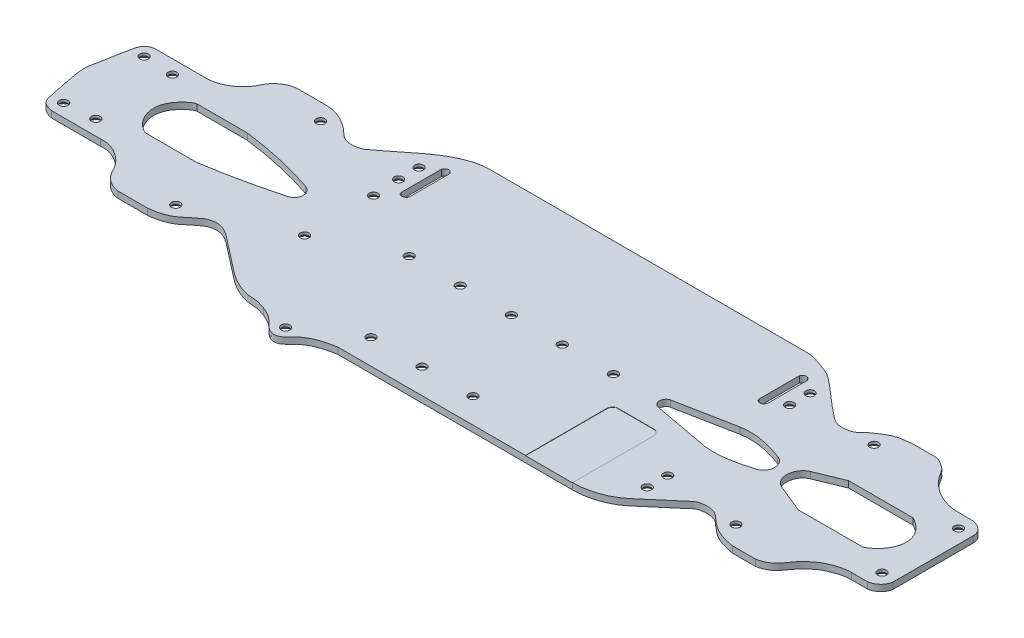
SolidWorks part; units mm, degrees
material "Zoltek Panex 33"
ref_plane "Front Plane" through (0, 0, 0) normal (0, 0, 1) x (1, 0, 0)
ref_plane "Top Plane" through (0, 0, 0) normal (0, 1, 0) x (1, 0, 0)
ref_plane "Right Plane" through (0, 0, 0) normal (1, 0, 0) x (0, 0, -1)
sketch "Sketch1" plane through (0, 0, 0) normal (0, 1, 0) x (1, 0, 0)
  line L0 (36.9075, 54.8824) -> (56.619, 54.8824)
  line L5 (-505.162, 146.0143) -> (342.4194, 309.6238) construction
  line L6 (291.5512, 9.8532) -> (300.5935, 9.8532)
  line L7 (323.9187, 24.1186) -> (330.3042, 24.1186)
  line L8 (335.3376, 29.0345) -> (335.3376, 60.2672)
  line L9 (330.5501, 65.4209) -> (323.8702, 65.4209)
  line L10 (300.1848, 79.7219) -> (292.3112, 79.7219)
  line L11 (62.1058, 79.7259) -> (51.43, 79.7259)
  line L13 (10.7454, 24.1146) -> (29.9596, 24.1146)
  line L14 (51.0209, 9.8532) -> (62.5548, 9.8532)
  line L15 (147.063, -0.0125) -> (238.9152, -0.0125)
  line L16 (116.3922, 89.9875) -> (241.4126, 89.9875)
  line L17 (9.9428, 65.3756) -> (29.4609, 65.3756)
  line L18 (106.9523, 80.6662) -> (106.9523, 64.8635)
  line L19 (110.0606, 80.6662) -> (110.0606, 64.8635)
  line L20 (247.0438, 80.6662) -> (247.0438, 64.8635)
  line L21 (250.1871, 80.6662) -> (250.1871, 64.8635)
  line L22 (220.4502, -0.0125) -> (220.4502, 31.35)
  line L23 (238.9152, -0.0125) -> (238.9152, 31.35)
  line L24 (222, 34.0566) -> (237, 34.0566)
  line L25 (220.4502, -0.0125) -> (238.9152, -0.0125)
  line L27 (56.619, 34.9418) -> (36.9075, 34.9418)
  line L29 (317.5252, 34.9418) -> (292.3112, 34.9418)
  line L31 (292.3112, 54.6841) -> (317.5252, 54.6841)
  line L33 (292.3112, 54.6841) -> (281.6573, 50.3113)
  line L34 (292.3112, 34.9418) -> (281.6573, 39.2887)
  line L35 (2.8407, 44.9982) -> (335.3376, 44.6509)
  circle A7 centre (255.1, 13) radius 1.5
  circle A8 centre (255.1, 21) radius 1.5
  circle A9 centre (255.1, 68.8) radius 1.5
  circle A10 centre (255.1, 76.8) radius 1.5
  circle A11 centre (285.1, 71.85) radius 1.5
  circle A12 centre (285.1, 17.75) radius 1.5
  circle A13 centre (170.1, 9.8) radius 1.5
  circle A14 centre (150.1, 9.8) radius 1.5
  circle A15 centre (150.1, 44.8) radius 1.5
  circle A16 centre (130.1, 44.8) radius 1.5
  circle A17 centre (170.1, 44.8) radius 1.5
  circle A18 centre (190.1, 44.7454) radius 1.5
  circle A19 centre (210.1, 44.8) radius 1.5
  circle A20 centre (130.1, -3.6) radius 1.5
  circle A21 centre (102.6, 31.35) radius 1.5
  circle A22 centre (102.6, 58.35) radius 1.5
  circle A23 centre (102, 68.75) radius 1.5
  circle A24 centre (102, 76.75) radius 1.5
  circle A25 centre (67, 73.2) radius 1.5
  circle A26 centre (67, 16.5) radius 1.5
  circle A27 centre (22.2, 30) radius 1.5
  circle A28 centre (10.5, 29.1) radius 1.5
  circle A29 centre (10.5, 60.6) radius 1.5
  circle A30 centre (22.2, 60) radius 1.5
  circle A32 centre (330, 60) radius 1.5
  circle A33 centre (330, 30) radius 1.5
  circle A34 centre (190.1, 9.8) radius 1.5
  spline S0 degree 3 poles (238.9152, -0.0125) (242.5691, -0.0579) (247.678, 1.0476) (253.755, 4.2222) (257.449, 7.3728) (262.1815, 11.5538) (266.2457, 14.8282) (269.3805, 17.7348) (271.4097, 18.2316) (273.2247, 18.4304) (275.0039, 18.2101) (276.5606, 17.8019) (277.9794, 16.876) (279.2967, 15.7521) (280.6133, 14.5036) (282.0863, 13.2873) (283.8936, 12.1947) (286.9859, 10.7524) (289.6755, 10.2087) (291.5512, 9.8532) knots 0 0 0 0 0.180867 0.249762 0.337799 0.419905 0.561881 0.598784 0.626796 0.663132 0.688826 0.715104 0.741927 0.771676 0.80083 0.831669 0.865959 0.90501 1 1 1 1
  spline S1 degree 3 poles (300.5935, 9.8532) (301.5159, 9.9919) (303.5768, 10.6563) (306.0873, 12.2304) (308.2319, 15.2673) (310.0767, 17.9996) (312.7538, 20.0495) (314.5484, 21.4716) (316.7163, 22.4429) (318.7469, 23.2906) (321.2097, 23.9637) (322.8836, 24.1173) (323.9187, 24.1186) knots 0 0 0 0 0.097852 0.22965 0.302407 0.489628 0.573653 0.657741 0.730732 0.823623 0.890489 1 1 1 1
  spline S2 degree 3 poles (330.3042, 24.1186) (332.7512, 24.5173) (334.9418, 26.3459) (335.3376, 29.0345) knots 0 0 0 0 1 1 1 1
  spline S3 degree 2 poles (335.3376, 60.2672) (335.3816, 64.063) (330.5501, 65.4209) knots 0 0 0 1 1 1
  spline S4 degree 3 poles (323.8702, 65.4209) (317.6191, 65.565) (310.7059, 69.8359) (307.2106, 76.1983) (306.2096, 77.2959) (304.0985, 78.7645) (302.1467, 79.9343) (300.1848, 79.7219) knots 0 0 0 0 0.659857 0.730605 0.7617 0.815046 1 1 1 1
  spline S5 degree 3 poles (292.3112, 79.7219) (290.5159, 79.5322) (287.6509, 79.2857) (284.3358, 77.8344) (282.2459, 76.4816) (280.3848, 75.294) (278.8439, 73.942) (277.2108, 72.2238) (274.5974, 71.4915) (270.3152, 71.1989) (266.9358, 74.269) (263.7663, 76.7063) (259.9041, 80.2085) (255.9498, 83.596) (251.5323, 86.9064) (247.1548, 88.4495) (243.8639, 89.76) (241.4126, 89.9875) knots 0 0 0 0 0.092837 0.144175 0.182811 0.2199 0.256495 0.2875 0.338957 0.390178 0.499999 0.551883 0.597061 0.764972 0.818812 0.876527 1 1 1 1
  spline S6 degree 3 poles (116.3922, 89.9875) (111.1238, 89.9151) (99.5657, 84.7871) (90.7474, 76.1473) (84.7297, 72.0114) (84.0862, 71.8126) (82.5975, 71.3511) (80.5062, 71.18) (77.9181, 71.73) (75.8117, 73.3979) (73.8851, 75.3212) (71.5874, 76.9085) (67.9396, 78.9639) (64.5002, 79.8063) (62.1058, 79.7259) knots 0 0 0 0 0.25124 0.591867 0.594714 0.603635 0.624035 0.670442 0.703263 0.749584 0.797255 0.835489 0.884027 1 1 1 1
  spline S7 degree 3 poles (51.43, 79.7259) (48.9162, 79.5899) (45.8957, 77.9531) (43.3665, 74.793) (42.5236, 72.7345) (39.0955, 67.7976) (34.0151, 65.2337) (29.4609, 65.3756) knots 0 0 0 0 0.273781 0.345825 0.439759 0.514564 1 1 1 1
  spline S8 degree 3 poles (106.9523, 80.6662) (107.178, 81.3131) (108.5648, 82.386) (109.877, 81.2748) (110.0606, 80.6662) knots 0 0 0 0 0.518455 1 1 1 1
  spline S9 degree 3 poles (9.9428, 65.3756) (9.1797, 65.2605) (7.421, 64.8234) (5.8756, 62.3433) (5.2135, 58.7384) (4.525, 55.0046) (3.6673, 50.2001) (2.5878, 45.8732) (3.0955, 40.9401) (4.4744, 35.1512) (5.07, 30.241) (6.6394, 25.2333) (9.2545, 24.3483) (10.7454, 24.1146) knots 0 0 0 0 0.050552 0.108721 0.174135 0.286411 0.351534 0.487562 0.568362 0.666393 0.869136 0.884827 1 1 1 1
  spline S10 degree 3 poles (29.9596, 24.1146) (32.4035, 24.4101) (36.0701, 23.1624) (40.5861, 19.7834) (42.5066, 17.113) (43.2431, 15.3367) knots 0 0 0 0 0.430734 0.657674 1 1 1 1
  spline S11 degree 3 poles (43.2431, 15.3367) (43.7858, 14.4087) (45.7083, 11.699) (48.8311, 10.1461) (51.0209, 9.8532) knots 0 0 0 0 0.328355 1 1 1 1
  spline S12 degree 3 poles (62.5548, 9.8532) (65.1521, 10.093) (70.44, 11.2541) (74.806, 15.7303) (78.3485, 18.0472) (80.6444, 18.4119) (83.2095, 18.3293) (86.9926, 16.4138) (91.3186, 12.6696) (97.4232, 8.1597) (103.8547, 2.6603) (110.7465, -0.098) (116.0567, -0.0855) (118.0635, -1.0496) (119.2709, -1.3396) knots 0 0 0 0 0.123328 0.23786 0.286113 0.315954 0.34432 0.404093 0.506753 0.610976 0.755968 0.899757 0.941962 1 1 1 1
  spline S13 degree 3 poles (119.2709, -1.3396) (121.3553, -2.0922) (123.9702, -3.6707) (126.5526, -6.5825) (128.2349, -7.9778) (130.4389, -8.357) (132.1224, -7.8785) (133.8322, -6.3523) (137.5632, -2.1228) (143.1042, -0.6228) (147.063, -0.0125) knots 0 0 0 0 0.207535 0.273275 0.364647 0.401236 0.478196 0.516217 0.613576 1 1 1 1
  spline S14 degree 3 poles (106.9523, 64.8635) (106.9304, 64.3038) (107.5873, 63.707) (109.0244, 63.5667) (109.8466, 64.2499) (110.0606, 64.8635) knots 0 0 0 0 0.365317 0.535859 1 1 1 1
  spline S15 degree 3 poles (247.0438, 80.6662) (247.3036, 81.2441) (248.7176, 82.4836) (249.9296, 81.1607) (250.1871, 80.6662) knots 0 0 0 0 0.528439 1 1 1 1
  spline S16 degree 3 poles (247.0438, 64.8635) (247.1821, 64.1566) (247.9117, 63.6671) (249.361, 63.5911) (249.8607, 64.4955) (250.1871, 64.8635) knots 0 0 0 0 0.451333 0.577502 1 1 1 1
  spline S17 degree 2 poles (220.4502, 31.35) (220.2621, 33.2075) (222, 34.0566) knots 0 0 0 1 1 1
  spline S18 degree 2 poles (238.9152, 31.35) (239.114, 33.4036) (237, 34.0566) knots 0 0 0 1 1 1
  spline S19 degree 3 poles (36.9075, 54.8824) (35.5945, 54.564) (33.7993, 52.9765) (31.0983, 50.097) (28.4348, 43.0418) (32.5012, 36.3847) (36.9075, 34.9418) knots 0 0 0 0 0.154255 0.275825 0.463553 1 1 1 1
  spline S20 degree 2 poles (56.619, 54.8824) (71.6707, 53.0328) (86.0629, 48.2282) knots 0 0 0 1 1 1
  spline S21 degree 2 poles (56.619, 34.9418) (71.5108, 37.2842) (86.0629, 41.2282) knots 0 0 0 1 1 1
  spline S22 degree 3 poles (86.0629, 48.2282) (86.8688, 47.8915) (88.2855, 46.9908) (89.2367, 43.8002) (87.6689, 41.6175) (86.0629, 41.2282) knots 0 0 0 0 0.286266 0.503501 1 1 1 1
  spline S23 degree 3 poles (292.3112, 54.6841) (288.437, 53.094) (285.5604, 51.8291) (281.6573, 50.3113) knots 0 0 0 0 1 1 1 1
  spline S24 degree 3 poles (281.6573, 50.3113) (277.4513, 48.5722) (276.404, 41.3626) (281.6573, 39.2887) knots 0 0 0 0 1 1 1 1
  spline S25 degree 3 poles (317.5252, 54.6841) (320.088, 53.4189) (323.5801, 50.4086) (325.3568, 41.8967) (321.1396, 36.6666) (317.5252, 34.9418) knots 0 0 0 0 0.347635 0.503598 1 1 1 1
  spline S26 degree 1 poles (230.0759, 47.1939) (252.7849, 51.6236) knots 0 0 1 1
  spline S27 degree 1 poles (230.0759, 42.3265) (252.7849, 38.1236) knots 0 0 1 1
  spline S28 degree 3 poles (252.7849, 51.6236) (258.6536, 52.6702) (264.6944, 50.9658) (270.1605, 49.0098) knots 0 0 0 0 1 1 1 1
  spline S29 degree 3 poles (270.1605, 49.0098) (273.8462, 47.9874) (274.6644, 42.2514) (270.5713, 40.5836) knots 0 0 0 0 1 1 1 1
  spline S30 degree 3 poles (252.7849, 38.1236) (258.797, 37.3702) (264.846, 38.8684) (270.5713, 40.5836) knots 0 0 0 0 1 1 1 1
  spline S31 degree 3 poles (230.0759, 47.1939) (228.9661, 46.9875) (227.3335, 44.7551) (228.9579, 42.5388) (230.0759, 42.3265) knots 0 0 0 0 0.499752 1 1 1 1
  point P250 (0, 0)
  point P253 (0, 0)
  dimension "D3" = 20
  dimension "D9" = 30
  dimension "D14" = 8
  dimension "D1" = 54.1
  dimension "D2" = 56.7
  dimension "D4" = 20
  dimension "D5" = 20
  dimension "D6" = 20
  dimension "D7" = 35
  dimension "D8" = 35
  dimension "D10" = 31.5
  dimension "D11" = 8
  dimension "D12" = 27
  dimension "D13" = 20
  dimension "D15" = 30
  dimension "D16" = 8
  dimension "D17" = 20
  dimension "D18" = 7
extrude "Boss-Extrude2" add sketch "Sketch1" along normal blind 2.5
sketch "Sketch3" plane through (0, 2.5, 0) normal (0, 1, 0) x (1, 0, 0)
  line L0 (220.4502, -0.0125) -> (220.4502, 31.35)
  line L1 (238.9152, -0.0125) -> (238.9152, 31.35)
  line L2 (222, 34.0566) -> (237, 34.0566)
  line L3 (220.4502, -0.0125) -> (238.9152, -0.0125)
  parabola Q0 (220.4502, 31.35) -> (222, 34.0566) focus (221.6928, 32.3634) apex (220.7031, 32.8816) construction
  spline S0 degree 2 poles (220.4502, 31.35) (220.2706, 33.2237) (222, 34.0566) knots 0 0 0 1 1 1
  spline S1 degree 2 poles (238.9152, 31.35) (239.114, 33.4036) (237, 34.0566) knots 0 0 0 1 1 1
extrude "Cut-Extrude1" cut sketch "Sketch3" against normal blind 0.1
hole_wizard "CSK for M3 Flat Head Machine Screw2" positions "Sketch7" profile "Sketch8" countersink size "M3" standard "ANSI Metric" end condition through all
sketch "Sketch7" plane through (0, 0, 0) normal (0, -1, 0) x (-1, 0, 0)
  point P0 (-330, 60)
sketch "Sketch8" plane through (330, 0, -60) normal (1, 0, 0) x (0, 0, -1)
  line L0 (0, 0) -> (0, 2.5)
  line L1 (0, 2.5) -> (1.7, 2.5)
  line L2 (1.7, 2.5) -> (1.7, 1.45)
  line L3 (1.7, 1.45) -> (3.15, 0)
  line L5 (3.15, 0) -> (0, 0)
  line L6 (-1.7, 1.45) -> (-3.15, 0) construction
  line L11 (0, -6.35) -> (0, 107.95) construction
  dimension "Thru Hole Dia." = 3.4
  dimension "Thru Hole Depth" = 2.5
  dimension "Near C'Sink Dia." = 6.3
  dimension "Near C'Sink Angle" = 90
hole_wizard "CSK for M3 Flat Head Machine Screw1" positions "Sketch13" profile "Sketch14" countersink size "M3" standard "ANSI Metric" end condition through all
sketch "Sketch13" plane through (0, 0, 0) normal (0, -1, 0) x (-1, 0, 0)
  point P0 (-330, 30)
sketch "Sketch14" plane through (330, 0, -30) normal (1, 0, 0) x (0, 0, -1)
  line L0 (0, 0) -> (0, 2.5)
  line L1 (0, 2.5) -> (1.7, 2.5)
  line L2 (1.7, 2.5) -> (1.7, 1.45)
  line L3 (1.7, 1.45) -> (3.15, 0)
  line L5 (3.15, 0) -> (0, 0)
  line L6 (-1.7, 1.45) -> (-3.15, 0) construction
  line L11 (0, -6.35) -> (0, 107.95) construction
  dimension "Thru Hole Dia." = 3.4
  dimension "Thru Hole Depth" = 2.5
  dimension "Near C'Sink Dia." = 6.3
  dimension "Near C'Sink Angle" = 90
hole_wizard "CSK for M3 Flat Head Machine Screw3" positions "Sketch16" profile "Sketch17" countersink size "M3" standard "ANSI Metric" end condition through all
sketch "Sketch16" plane through (0, 0, 0) normal (0, -1, 0) x (-1, 0, 0)
  point P0 (-285.1, 71.85)
sketch "Sketch17" plane through (285.1, 0, -71.85) normal (1, 0, 0) x (0, 0, -1)
  line L0 (0, 0) -> (0, 2.5)
  line L1 (0, 2.5) -> (1.7, 2.5)
  line L2 (1.7, 2.5) -> (1.7, 1.45)
  line L3 (1.7, 1.45) -> (3.15, 0)
  line L5 (3.15, 0) -> (0, 0)
  line L6 (-1.7, 1.45) -> (-3.15, 0) construction
  line L11 (0, -6.35) -> (0, 107.95) construction
  dimension "Thru Hole Dia." = 3.4
  dimension "Thru Hole Depth" = 2.5
  dimension "Near C'Sink Dia." = 6.3
  dimension "Near C'Sink Angle" = 90
hole_wizard "CSK for M3 Flat Head Machine Screw4" positions "Sketch18" profile "Sketch19" countersink size "M3" standard "ANSI Metric" end condition through all
sketch "Sketch18" plane through (0, 0, 0) normal (0, -1, 0) x (-1, 0, 0)
  point P0 (-285.1, 17.75)
  point P3 (-255.1, 76.8)
  point P6 (-255.1, 68.8)
  point P9 (-255.1, 21)
  point P12 (-255.1, 13)
  point P15 (-210.1, 44.8)
  point P18 (-190.1, 9.8)
sketch "Sketch19" plane through (285.1, 0, -17.75) normal (1, 0, 0) x (0, 0, -1)
  line L0 (0, 0) -> (0, 2.5)
  line L1 (0, 2.5) -> (1.7, 2.5)
  line L2 (1.7, 2.5) -> (1.7, 1.45)
  line L3 (1.7, 1.45) -> (3.15, 0)
  line L5 (3.15, 0) -> (0, 0)
  line L6 (-1.7, 1.45) -> (-3.15, 0) construction
  line L11 (0, -6.35) -> (0, 107.95) construction
  dimension "Thru Hole Dia." = 3.4
  dimension "Thru Hole Depth" = 2.5
  dimension "Near C'Sink Dia." = 6.3
  dimension "Near C'Sink Angle" = 90
hole_wizard "CSK for M3 Flat Head Machine Screw5" positions "Sketch20" profile "Sketch21" countersink size "M3" standard "ANSI Metric" end condition through all
sketch "Sketch20" plane through (0, 0, 0) normal (0, -1, 0) x (-1, 0, 0)
  point P0 (-190.1, 44.7454)
  point P3 (-170.1, 9.8)
  point P6 (-170.1, 44.8)
  point P9 (-150.1, 44.8)
  point P12 (-150.1, 9.8)
  point P15 (-130.1, -3.6)
  point P18 (-130.1, 44.8)
  point P21 (-102.6, 31.35)
  point P24 (-102.6, 58.35)
  point P27 (-102, 68.75)
  point P30 (-102, 76.75)
  point P33 (-67, 73.2)
  point P36 (-67, 16.5)
  point P39 (-22.2, 30)
  point P42 (-22.2, 60)
  point P45 (-10.5, 60.6)
  point P48 (-10.5, 29.1)
sketch "Sketch21" plane through (190.1, 0, -44.7454) normal (1, 0, 0) x (0, 0, -1)
  line L0 (0, 0) -> (0, 2.5)
  line L1 (0, 2.5) -> (1.7, 2.5)
  line L2 (1.7, 2.5) -> (1.7, 1.45)
  line L3 (1.7, 1.45) -> (3.15, 0)
  line L5 (3.15, 0) -> (0, 0)
  line L6 (-1.7, 1.45) -> (-3.15, 0) construction
  line L11 (0, -6.35) -> (0, 107.95) construction
  dimension "Thru Hole Dia." = 3.4
  dimension "Thru Hole Depth" = 2.5
  dimension "Near C'Sink Dia." = 6.3
  dimension "Near C'Sink Angle" = 90
